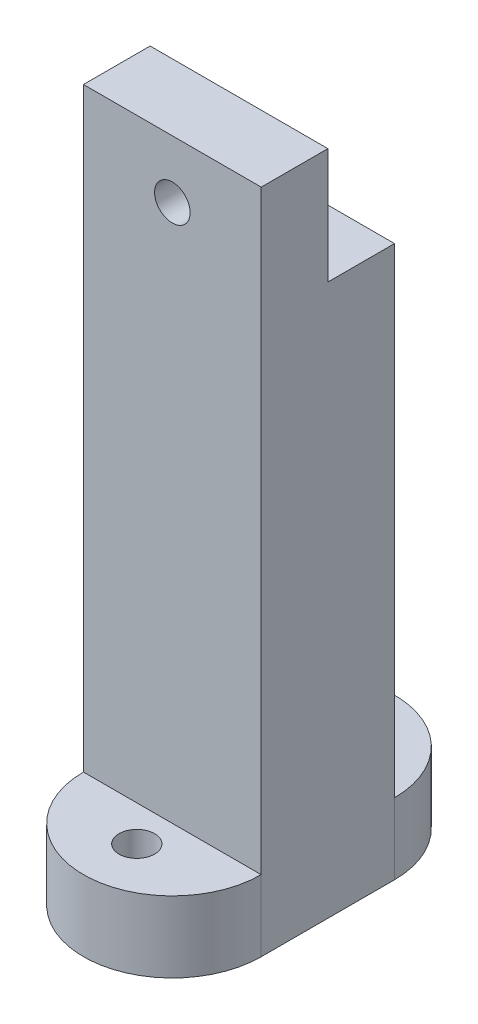
SolidWorks part; units mm, degrees
ref_plane "Front Plane" through (0, 0, 0) normal (0, 0, 1) x (1, 0, 0)
ref_plane "Top Plane" through (0, 0, 0) normal (0, 1, 0) x (1, 0, 0)
ref_plane "Right Plane" through (0, 0, 0) normal (1, 0, 0) x (0, 0, -1)
sketch "Sketch1" plane through (0, 0, 0) normal (0, 0, 1) x (1, 0, 0)
  line L1 (-10, 37.5) -> (10, 37.5)
  line L2 (-10, 37.5) -> (-10, -37.5)
  line L3 (-10, -37.5) -> (10, -37.5)
  line L4 (10, 37.5) -> (10, -37.5)
  line L5 (-10, 37.5) -> (10, -37.5) construction
  line L6 (-10, -37.5) -> (10, 37.5) construction
  point P0 (0, 0)
  dimension "D1" = 75
  dimension "D2" = 20
extrude "Boss-Extrude1" add sketch "Sketch1" along normal blind 15
sketch "Sketch2" plane through (0, -37.5, 0) normal (0, -1, 0) x (1, 0, 0)
  line L0 (-10, 0) -> (10, 0)
  line L1 (10, 7.5) -> (-25.2549, 7.5) construction
  line L2 (10, 15) -> (10, 0) construction
  line L3 (-10, 15) -> (10, 15)
  arc A0 (-10, 0) -> (10, 0) centre (0, 0) ccw
  circle A1 centre (0, -4) radius 2
  circle A2 centre (0, 19) radius 2
  arc A3 (-10, 15) -> (10, 15) centre (0, 15) cw
  dimension "D1" = 4
  dimension "D2" = 4
extrude "Boss-Extrude2" add sketch "Sketch2" against normal blind 8
sketch "Sketch3" plane through (0, 37.5, 0) normal (0, 1, 0) x (1, 0, 0)
  line L0 (-10, -15) -> (-10, 0) construction
  line L1 (10, 0) -> (-10, 0)
  line L2 (10, 0) -> (10, -7.5)
  line L3 (10, -7.5) -> (-10, -7.5)
  line L4 (-10, 0) -> (-10, -7.5)
extrude "Cut-Extrude1" cut sketch "Sketch3" against normal blind 13
sketch "Sketch4" plane through (0, 0, 7.5) normal (0, 0, -1) x (-1, 0, 0)
  line L0 (10, 24.5) -> (-10, 24.5) construction
  circle A0 centre (0, 31) radius 2
  point P5 (0, 24.5)
  dimension "D1" = 4
  dimension "D2" = 6.5
extrude "Cut-Extrude2" cut sketch "Sketch4" against normal blind 13
